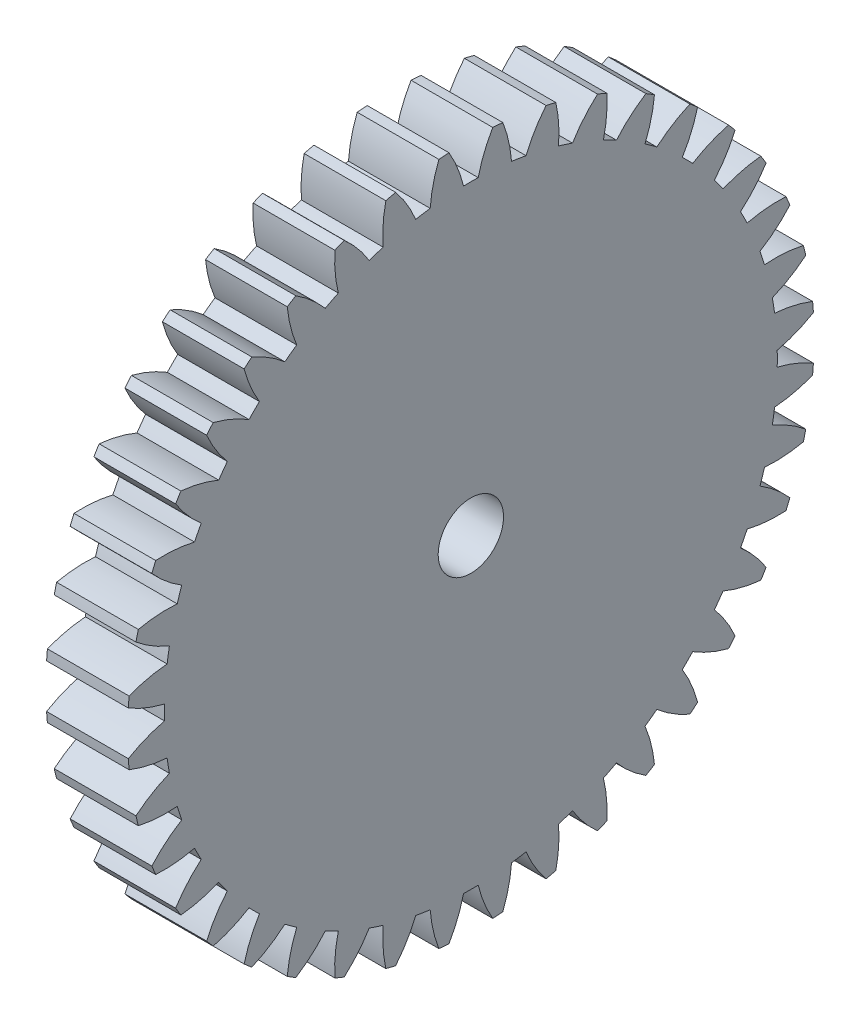
SolidWorks part; units mm, degrees
ref_plane "Plane1" through (0, 0, 0) normal (0, 0, 1) x (1, 0, 0)
ref_plane "Plane2" through (0, 0, 0) normal (0, 1, 0) x (1, 0, 0)
ref_plane "Plane3" through (0, 0, 0) normal (1, 0, 0) x (0, 0, -1)
sketch "HoldingSke" plane through (0, 0, 0) normal (0, 1, 0) x (1, 0, 0)
  line L0 (0, 0) -> (0.766, -0.6428)
  line L1 (-15, 0) -> (100, 0) construction
  line L2 (0, 0) -> (-2.1039, 2.3779)
  line L3 (0, 0) -> (-11.863, 4.5341)
  line L4 (0, 0) -> (6.6156, 5.5511)
  line L5 (0, 0) -> (-46.8476, -17.4728)
  line L6 (0, 0) -> (-4.1448, -2.7965)
  line L7 (-2.1039, 2.3779) -> (8.6586, 51.2059)
  line L8 (-76.2, 54.61) -> (-75.5, 54.61)
  line L9 (-71.009, 38.7566) -> (-53.1078, 45.2721)
  line L10 (-76.2, 71.12) -> (104.1128, 71.12)
  line L11 (0, 0) -> (-5, 0)
  line L12 (-76.2, 101.6) -> (-76.162, 101.6)
  line L13 (24.9733, 27.94) -> (52.9518, 28.4284)
  line L14 (24.9733, 27.94) -> (24.9743, 27.94)
  line L15 (24.9733, 27.94) -> (100.4006, 29.5858)
  line L16 (-63.627, -1) -> (-12.827, -1)
  circle A0 centre (0, 0) radius 2
  circle A1 centre (0, 0) radius 18.749
  circle A2 centre (0, 0) radius 37.5
  circle A3 centre (0, 0) radius 2
  dimension "MHD" = 37.498
  dimension "Hub_dia" = 75
  dimension "Bore" = 4
  dimension "MBD" = 4
  dimension "Num_teeth" = 40
  dimension "Pitch" = 1
  dimension "Overall_len" = 50
  dimension "Show_teeth" = 40
  dimension "Thickness" = 5
  dimension "OAL" = 50.0001
  dimension "T_dim" = 0.7
  dimension "Ap" = 20
  dimension "H" = 19.05
  dimension "Pitch_radius" = 180.3128
  dimension "Width" = 5
  dimension "Backlash" = 0.038
  dimension "Addendum_fac" = 1
  dimension "Dedendum_fac" = 1.25
  dimension "Clearance_fac" = 0.25
  dimension "Dedendum_add" = 0.001
  dimension "Module" = 1
sketch "BasProSke" plane through (0, 0, 0) normal (0, 1, 0) x (1, 0, 0)
  line L0 (-10, 0) -> (60, 0) construction
  line L1 (0, 0) -> (0, 21)
  line L2 (0, 0) -> (5, 0)
  line L3 (5, 0) -> (5, 21)
  line L4 (5, 21) -> (0, 21)
  dimension "Thickness" = 5
  dimension "Diameter" = 42
revolve "Base-Revolve" add sketch "BasProSke" angle 360 about L0
sketch "TooCutSke" plane through (0, 0, 0) normal (1, 0, 0) x (0, 0, -1)
  line L1 (0, 0) -> (0, 107) construction
  line L2 (0, 0) -> (-0.8517, 19.9819) construction
  line L3 (0, 0) -> (-3.1363, 39.8509) construction
  line L4 (-0.8517, 19.9819) -> (-1.5682, 19.9255) construction
  arc A0 (0.4487, 18.7436) -> (-0.4487, 18.7436) centre (0, 0) ccw
  arc A1 (1.3547, 20.9817) -> (-1.3547, 20.9817) centre (0, 0) ccw
  circle A2 centre (0, 0) radius 20 construction
  circle A3 centre (0, 0) radius 18.7939 construction
  arc A4 (-0.4487, 18.7436) -> (-1.3547, 20.9817) centre (-8.2322, 16.895) ccw
  arc A5 (1.3547, 20.9817) -> (0.4487, 18.7436) centre (8.2322, 16.895) ccw
  dimension "Root_dia" = 37.498
  dimension "Overcut_dia" = 42.0508
  dimension "Pitch_dia" = 40
  dimension "Base_dia" = 37.5877
  dimension "Flank_rad" = 8
  dimension "Half_ang" = 4.5
  dimension "Half_CT" = 0.7187
extrude "ToothCut" cut sketch "TooCutSke" along normal through all
fillet "Breaks" [suppressed] radius 0.02
fillet "RootFillets" [suppressed] radius 0.251
pattern_circular "TeethCuts" count 40 every 9 about axis through (-10, 0, 0) along (1, 0, 0) of "ToothCut", "RootFillets", "Breaks"
sketch "HubNeaOneSke" plane through (0, 0, 0) normal (-1, 0, 0) x (0, 0, 1)
  circle A0 centre (0, 0) radius 18.749
  dimension "Diameter" = 37.498
extrude "HubNearOne" [suppressed] add sketch "HubNeaOneSke" along normal blind 45.0001
sketch "HubNeaBotSke" plane through (0, 0, 0) normal (-1, 0, 0) x (0, 0, 1)
  circle A0 centre (0, 0) radius 18.749
  dimension "Diameter" = 37.498
extrude "HubNearBoth" [suppressed] add sketch "HubNeaBotSke" along normal blind 22.5
ref_plane "FarPln" through (5, 0, 0) normal (1, 0, 0) x (0, 0, -1)
sketch "HubFarSke" plane through (5, 0, 0) normal (1, 0, 0) x (0, 0, -1)
  circle A0 centre (0, 0) radius 18.749
  dimension "Diameter" = 37.498
extrude "HubFar" [suppressed] add sketch "HubFarSke" along normal blind 22.5
sketch "BorSke" plane through (0, 0, 0) normal (1, 0, 0) x (0, 0, -1)
  circle A0 centre (0, 0) radius 2
  dimension "Diameter" = 4
extrude "Bore" cut sketch "BorSke" along normal mid plane 100.0001
sketch "KeySke" plane through (0, 0, 0) normal (1, 0, 0) x (0, 0, -1)
  line L0 (-0.8, 0) -> (-0.8, 2.7)
  line L1 (-0.8, 2.7) -> (0.8, 2.7)
  line L2 (0.8, 2.7) -> (0.8, 0)
  line L3 (0, 0) -> (0, 34) construction
  line L4 (-0.8, 0) -> (0.8, 0)
  dimension "Offset" = 2.7
  dimension "Width" = 1.6
extrude "Keyway" [suppressed] cut sketch "KeySke" along normal mid plane 100.0001
pattern_circular "Keyway2" [suppressed] count 2 every 90 about axis through (-10, 0, 0) along (1, 0, 0)
equation "' \"Module@HoldingSke\" = 6.35"
equation "' \"Num_teeth@HoldingSke\" = 12"
equation "' \"Ap@HoldingSke\" =  20"
equation "' \"Ap@HoldingSke\" = 20"
equation "' \"Width@HoldingSke\" = 0.5 * 25.4"
equation "' \"Hub_dia@HoldingSke\"= 1 * 25.4"
equation "' \"Hub_dia@HoldingSke\" = 1 * 25.4"
equation "' \"Overall_len@HoldingSke\" = 1.0 * 25.4"
equation "' \"Bore@HoldingSke\" = 0.75 * 25.4"
equation "' \"T_dim@HoldingSke\" = 0.1 * 25.4"
equation "' \"Width@KeySke\" = 0.25 * 25.4"
equation "' \"Show_teeth@HoldingSke\" = 13"
equation "' \"Backlash@HoldingSke\" = 0.009 * 25.4"
equation "' \"Addendum_fac@HoldingSke\" = 1.0"
equation "' \"Dedendum_fac@HoldingSke\" = 1.25"
equation "' \"Dedendum_add@HoldingSke\" = 0.00005 * 25.4"
equation "' \"Clearance_fac@HoldingSke\" = 0.25"
equation "\"Pitch@HoldingSke\" = 1 / \"Module@HoldingSke\""
equation "\"Overcut_dia@TooCutSke\" = (\"Num_teeth@HoldingSke\" + 2 * \"Addendum_fac@HoldingSke\") / \"Pitch@HoldingSke\" + 0.002 * 25.4"
equation "\"Pitch_dia@TooCutSke\" = \"Num_teeth@HoldingSke\" / \"Pitch@HoldingSke\""
equation "\"Base_dia@TooCutSke\" = \"Num_teeth@HoldingSke\" / \"Pitch@HoldingSke\" * cos((\"Ap@HoldingSke\"  * 3.14159265 / 180))"
equation "\"Root_dia@TooCutSke\" = (\"Num_teeth@HoldingSke\" + 2) / \"Pitch@HoldingSke\" - 2 * (\"Addendum_fac@HoldingSke\" + \"Dedendum_fac@HoldingSke\") / \"Pitch@HoldingSke\" - \"Dedendum_add@HoldingSke\" * 2"
equation "\"Half_ang@TooCutSke\" = 180 / \"Num_teeth@HoldingSke\""
equation "\"Half_CT@TooCutSke\" = \"Num_teeth@HoldingSke\" / \"Pitch@HoldingSke\" * sin((3.14159265 / 2 / \"Num_teeth@HoldingSke\")) / 2 - 7 * \"Backlash@HoldingSke\" / 4"
equation "\"Flank_rad@TooCutSke\" = \"Num_teeth@HoldingSke\" / \"Pitch@HoldingSke\" / 5"
equation "\"Radius@RootFillets\" = \"Clearance_fac@HoldingSke\" / \"Pitch@HoldingSke\" + \"Dedendum_add@HoldingSke\""
equation "\"Break_rad@Breaks\" = 0.02 / \"Pitch@HoldingSke\""
equation "\"Thickness@HoldingSke\" = \"Width@HoldingSke\""
equation "\"OAL@HoldingSke\" = \"Thickness@HoldingSke\""
equation "\"MHD@HoldingSke\" = (\"Num_teeth@HoldingSke\" + 2) / \"Pitch@HoldingSke\" - 2 * (\"Addendum_fac@HoldingSke\" + \"Dedendum_fac@HoldingSke\")  / \"Pitch@HoldingSke\" - \"Dedendum_add@HoldingSke\" * 2"
equation "\"MBD@HoldingSke\" = (\"Num_teeth@HoldingSke\" + 2) / \"Pitch@HoldingSke\" - 2 * (\"Addendum_fac@HoldingSke\" + \"Dedendum_fac@HoldingSke\")  / \"Pitch@HoldingSke\" - \"Dedendum_add@HoldingSke\" * 2 - 0.002 * 25.4"
equation "\"MHD@HoldingSke\" = ((sgn( \"MHD@HoldingSke\" - \"Hub_dia@HoldingSke\" )-1)*( \"MHD@HoldingSke\" - \"Hub_dia@HoldingSke\" ))/-2+ \"Hub_dia@HoldingSke\""
equation "\"MBD@HoldingSke\" = ((sgn( \"MBD@HoldingSke\" - \"Bore@HoldingSke\" )-1)*( \"MBD@HoldingSke\" - \"Bore@HoldingSke\" ))/-2+ \"Bore@HoldingSke\""
equation "\"OAL@HoldingSke\" = ((sgn( \"OAL@HoldingSke\" - \"Overall_len@HoldingSke\" )+1)*( \"OAL@HoldingSke\" - \"Overall_len@HoldingSke\" ))/2 + \"Overall_len@HoldingSke\" + 0.000002 * 25.4"
equation "\"Num_teeth@TeethCuts\" = int( \"Show_teeth@HoldingSke\" ) + 1"
equation "\"Num_teeth@TeethCuts\" = ((sgn( \"Num_teeth@TeethCuts\" - \"Num_teeth@HoldingSke\" )-1)*( \"Num_teeth@TeethCuts\" - \"Num_teeth@HoldingSke\" ))/-2+ \"Num_teeth@HoldingSke\""
equation "\"Num_teeth@TeethCuts\" = ((sgn( \"Num_teeth@TeethCuts\" - 2.0)+1)*( \"Num_teeth@TeethCuts\" - 2.0))/2 +2.0"
equation "\"Angle@TeethCuts\" = 360.0 / \"Num_teeth@HoldingSke\""
equation "\"Diameter@BasProSke\" = (\"Num_teeth@HoldingSke\" + 2 * \"Addendum_fac@HoldingSke\") / \"Pitch@HoldingSke\""
equation "\"Thickness@BasProSke\"  = \"Thickness@HoldingSke\""
equation "' \"Fillet_rad@BasProSke\" =  \"Thickness@HoldingSke\" * 0.05"
equation "' \"Fillet_rad@BasProSke\" = \"Thickness@HoldingSke\" * 0.05"
equation "\"MHD@HoldingSke\" = ((sgn( \"MHD@HoldingSke\" - \"Root_dia@TooCutSke\" )-1)*( \"MHD@HoldingSke\" - \"Root_dia@TooCutSke\" ))/-2+ \"Root_dia@TooCutSke\""
equation "\"Diameter@HubNeaOneSke\" = \"MHD@HoldingSke\""
equation "\"Length@HubNearOne\" = \"OAL@HoldingSke\" - \"Thickness@BasProSke\""
equation "\"Diameter@HubNeaBotSke\" = \"MHD@HoldingSke\""
equation "\"Length@HubNearBoth\" = ( \"OAL@HoldingSke\" - \"Thickness@BasProSke\" ) / 2.0"
equation "\"Thickness@FarPln\" = \"Thickness@BasProSke\""
equation "\"Diameter@HubFarSke\" = \"MHD@HoldingSke\""
equation "\"Length@HubFar\" = ( \"OAL@HoldingSke\" - \"Thickness@BasProSke\" ) / 2.0"
equation "\"Diameter@BorSke\" = \"MBD@HoldingSke\""
equation "\"D1@Bore\" = \"OAL@HoldingSke\" * 2.0"
equation "\"D1@Keyway\" = \"OAL@HoldingSke\" * 2.0"
equation "\"Offset@KeySke\" = \"T_dim@HoldingSke\" + \"MBD@HoldingSke\" / 2.0"
